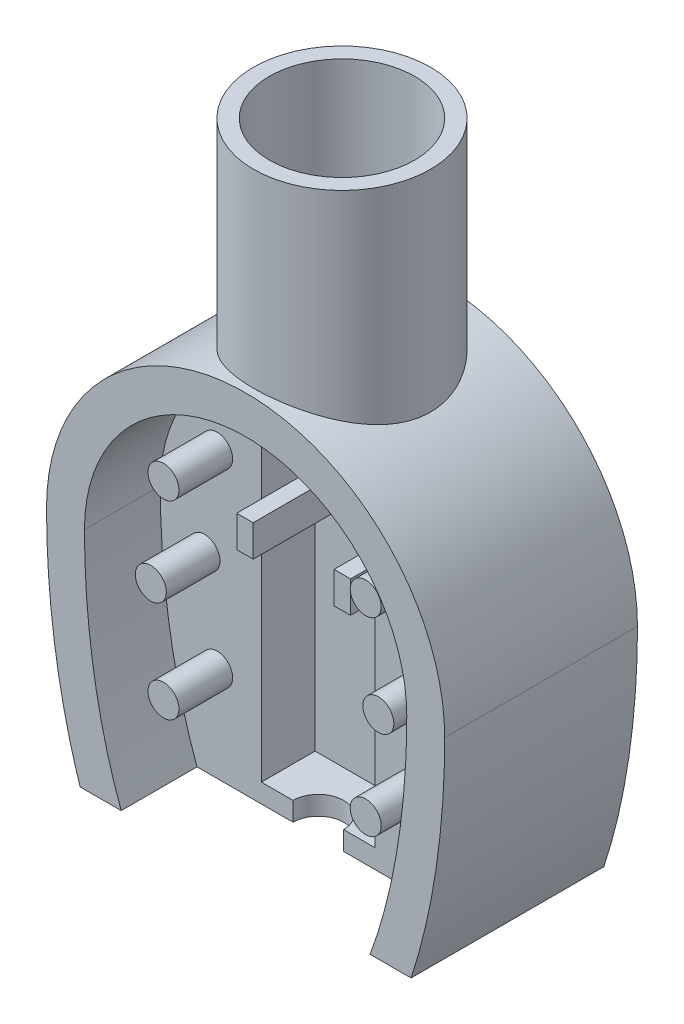
SolidWorks part; units mm, degrees
ref_plane "Alzado" through (0, 0, 0) normal (0, 0, 1) x (1, 0, 0)
ref_plane "Planta" through (0, 0, 0) normal (0, 1, 0) x (1, 0, 0)
ref_plane "Vista lateral" through (0, 0, 0) normal (1, 0, 0) x (0, 0, -1)
sketch "Croquis13" plane through (0, 0, 0) normal (0, 0, 1) x (1, 0, 0)
  line L0 (68.4697, -47.5577) -> (110.4435, -47.5577)
  line L1 (63.2785, -47.5577) -> (115.6347, -47.5577)
  arc A0 (115.9566, -11.9612) -> (62.9566, -11.9612) centre (89.4566, -11.9612) ccw
  arc A1 (120.9566, -11.9612) -> (57.9566, -11.9612) centre (89.4566, -11.9612) ccw
  ellipse E0 centre (89.4566, -11.9612) end of major axis (89.4566, -70.2612) minor radius 26.5 (62.9566, -11.9612) -> (68.4697, -47.5577) ccw
  ellipse E1 centre (89.4566, -11.9612) end of major axis (89.4566, -70.2612) minor radius 26.5 (110.4435, -47.5577) -> (115.9566, -11.9612) ccw
  ellipse E2 centre (89.4566, -11.9612) end of major axis (89.4566, -75.9612) minor radius 31.5 (115.6347, -47.5577) -> (120.9566, -11.9612) ccw
  ellipse E3 centre (89.4566, -11.9612) end of major axis (89.4566, -75.9612) minor radius 31.5 (57.9566, -11.9612) -> (63.2785, -47.5577) ccw
  point P28 (89.4566, -47.5577)
  dimension "D1" = 31.5
extrude "Saliente-Extruir2" add sketch "Croquis13" along normal blind 30.5 contours A1 E3 L1 E2
sketch "Croquis14" plane through (0, 0, 30.5) normal (0, 0, 1) x (1, 0, 0)
  line L0 (63.2785, -47.5577) -> (115.6347, -47.5577) construction
  circle A0 centre (89.4566, -11.9612) radius 25.5
  ellipse E0 centre (89.4566, -11.9612) end of major axis (89.4566, 44.0388) minor radius 25.5 (109.142, -47.5577) -> (114.9566, -11.9612) ccw
  ellipse E1 centre (89.4566, -11.9612) end of major axis (89.4566, 44.0388) minor radius 25.5 (63.9566, -11.9612) -> (69.7712, -47.5577) ccw
  line M4 (63.2785, -47.5577) -> (115.6347, -47.5577)
extrude "Cortar-Extruir1" cut sketch "Croquis14" against normal blind 12 contours A0 | A0 E1 E0 M4
ref_plane "Plano1" through (89.4566, 19.5388, 30.5) normal (0, 1, 0) x (1, 0, 0)
sketch "Croquis15" plane through (89.4566, 19.5388, 30.5) normal (0, 1, 0) x (1, 0, 0)
  line L2 (-31.5, 15.25) -> (31.5, 15.25) construction
  line L4 (-31.5, 0) -> (-31.5, 30.5) construction
  line L5 (31.5, 0) -> (31.5, 30.5) construction
  circle A0 centre (0, 15.25) radius 14
  dimension "D1" = 28
extrude "Saliente-Extruir3" add sketch "Croquis15" along normal blind 30 and the other way blind 4
sketch "Croquis16" plane through (0, 49.5388, 0) normal (0, 1, 0) x (1, 0, 0)
  circle A0 centre (89.4566, -15.25) radius 11.5
  dimension "D1" = 23
extrude "Cortar-Extruir2" cut sketch "Croquis16" against normal blind 25
sketch "Sketch1" plane through (0, -29.0577, 18.5) normal (0, 0, -1) x (-1, 0, 0)
  line L0 (-97.9566, 37.5) -> (-79.9566, 37.5)
  line L1 (-97.9566, 37.5) -> (-97.9566, -15.5)
  line L2 (-79.9566, 37.5) -> (-79.9566, -15.5)
  line L3 (-97.9566, -15.5) -> (-79.9566, -15.5)
  line L6 (-63.2785, -18.5) -> (-115.6347, -18.5) construction
  dimension "D1" = 18
  dimension "D2" = 53
  dimension "D3" = 3
  dimension "D4" = 16
extrude "Cut-Extrude1" cut sketch "Sketch1" along normal blind 8.5
sketch "Sketch2" plane through (0, -44.5577, 0) normal (0, -1, 0) x (1, 0, 0)
  line L2 (114.9566, 18.5) -> (63.9566, 18.5) construction
  line L3 (97.9566, 18.5) -> (79.9566, 18.5) construction
  circle A0 centre (88.9566, 18.5) radius 4
  point P2 (101.5964, 18.5)
  point P5 (86.8354, 18.5)
  point P8 (88.9566, 18.5)
  dimension "D1" = 8
extrude "Cut-Extrude2" cut sketch "Sketch2" along normal up to surface (3 mm away) up to face at (89.4566, -47.5577, 19.875)
sketch "Sketch3" plane through (0, 0, 18.5) normal (0, 0, 1) x (1, 0, 0)
  line L0 (69.7712, -47.5577) -> (84.9566, -47.5577) construction
  line L1 (79.9566, -44.5577) -> (79.9566, 8.4423) construction
  line L2 (79.9566, -44.5577) -> (79.9566, 8.4423) construction
  line L3 (97.9566, 8.4423) -> (97.9566, -44.5577) construction
  line L4 (97.9566, 8.4423) -> (97.9566, -44.5577) construction
  circle A0 centre (104.9566, -32.5577) radius 2.45
  circle A1 centre (104.9566, -2.5577) radius 2.45
  circle A2 centre (70.9566, -17.5577) radius 2.45
  circle A3 centre (106.9566, -17.5577) radius 2.45
  circle A4 centre (72.9566, -32.5577) radius 2.45
  circle A5 centre (72.9566, -2.5577) radius 2.45
  dimension "D6" = 4.9
  dimension "D1" = 15
  dimension "D2" = 30
  dimension "D3" = 45
  dimension "D4" = 7
  dimension "D5" = 9
  dimension "D7" = 7
  dimension "D8" = 9
extrude "Boss-Extrude1" add sketch "Sketch3" along normal blind 8.5
sketch "Sketch4" plane through (0, 0, 10) normal (0, 0, 1) x (1, 0, 0)
  line L0 (79.9566, -44.5577) -> (79.9566, 8.4423) construction
  line L1 (79.9566, -5.7577) -> (82.5566, -5.7577)
  line L2 (79.9566, -5.7577) -> (79.9566, -10.7577)
  line L3 (79.9566, -10.7577) -> (82.5566, -10.7577)
  line L4 (82.5566, -5.7577) -> (82.5566, -10.7577)
  line L5 (97.9566, 8.4423) -> (97.9566, -44.5577) construction
  line L6 (97.9566, -5.7577) -> (95.3566, -5.7577)
  line L7 (97.9566, -5.7577) -> (97.9566, -10.7577)
  line L8 (97.9566, -10.7577) -> (95.3566, -10.7577)
  line L9 (95.3566, -5.7577) -> (95.3566, -10.7577)
  line L10 (97.9566, -44.5577) -> (79.9566, -44.5577) construction
  dimension "D1" = 5
  dimension "D2" = 5
  dimension "D3" = 2.6
  dimension "D4" = 2.6
  dimension "D5" = 33.8
extrude "Boss-Extrude2" add sketch "Sketch4" along normal blind 12.4
